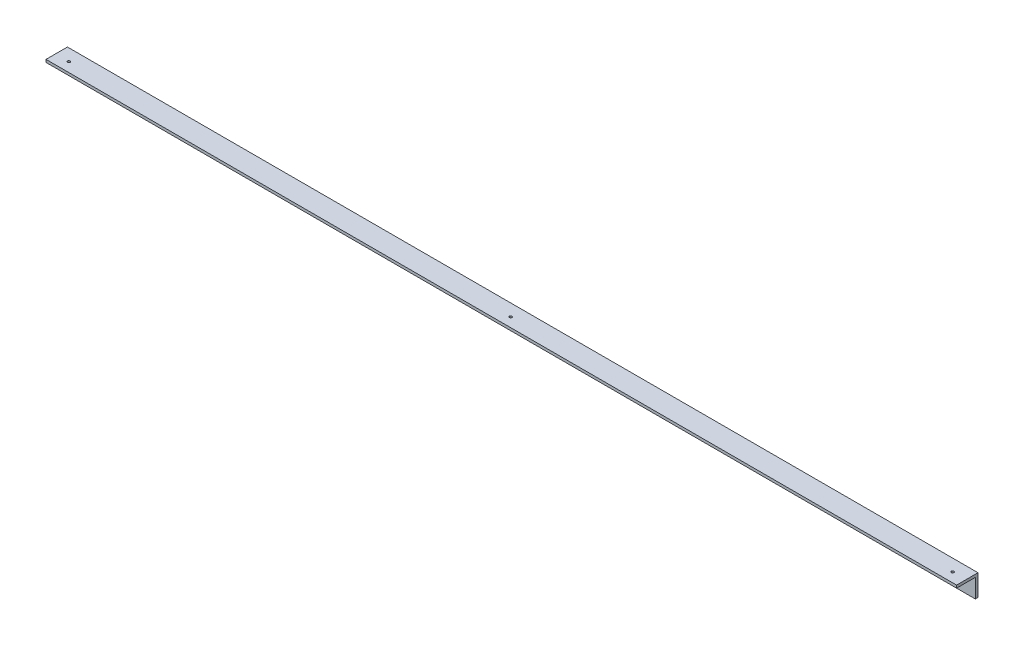
SolidWorks part; units mm, degrees
ref_plane "Alzado" through (0, 0, 0) normal (0, 0, 1) x (1, 0, 0)
ref_plane "Planta" through (0, 0, 0) normal (0, 1, 0) x (1, 0, 0)
ref_plane "Vista lateral" through (0, 0, 0) normal (1, 0, 0) x (0, 0, -1)
sketch "Croquis1" plane through (0, 0, 0) normal (0, 0, 1) x (1, 0, 0)
  line L0 (-50, 0) -> (-50, -40)
  line L1 (0, 0) -> (-50, 0)
  line L2 (3300, 0) -> (3350, 0)
  line L3 (-50, -40) -> (3350, -40)
  line L4 (3350, -40) -> (3350, 40)
  line L5 (3350, 40) -> (-50, 40)
  line L6 (-50, 40) -> (-50, 0)
  circle A0 centre (0, 0) radius 4.7625
  circle A1 centre (1650, 0) radius 4.765
  circle A2 centre (3300, 0) radius 4.765
  dimension "D4" = 9.525
  dimension "D5" = 9.53
  dimension "D6" = 9.53
  dimension "D1" = 3300
  dimension "D2" = 50
  dimension "D3" = 50
  dimension "D7" = 40
  dimension "D8" = 40
extrude "Saliente-Extruir1" add sketch "Croquis1" along normal blind 10
sketch "Croquis2" plane through (0, 0, 10) normal (0, 0, 1) x (1, 0, 0)
  line L0 (-50, 40) -> (-50, 30)
  line L1 (-50, 40) -> (-50, -40) construction
  line L2 (-50, 30) -> (3350, 30)
  line L3 (3350, -40) -> (3350, 40) construction
  line L4 (3350, 30) -> (3350, 40)
  line L5 (3350, 40) -> (-50, 40)
  dimension "D1" = 10
extrude "Saliente-Extruir2" add sketch "Croquis2" along normal blind 70
sketch "Croquis3" plane through (0, 30, 0) normal (0, -1, 0) x (1, 0, 0)
  line L0 (-50, 45) -> (0, 45) construction
  line L1 (-50, 80) -> (-50, 10) construction
  line L2 (0, 45) -> (1650, 45) construction
  line L3 (1650, 45) -> (3300, 45) construction
  circle A0 centre (3300, 45) radius 4.7625
  circle A1 centre (1650, 45) radius 4.7625
  circle A2 centre (0, 45) radius 4.7625
  dimension "D4" = 9.525
  dimension "D5" = 9.525
  dimension "D6" = 9.525
  dimension "D1" = 50
  dimension "D2" = 1650
  dimension "D3" = 1650
extrude "Cortar-Extruir1" cut sketch "Croquis3" against normal through all
